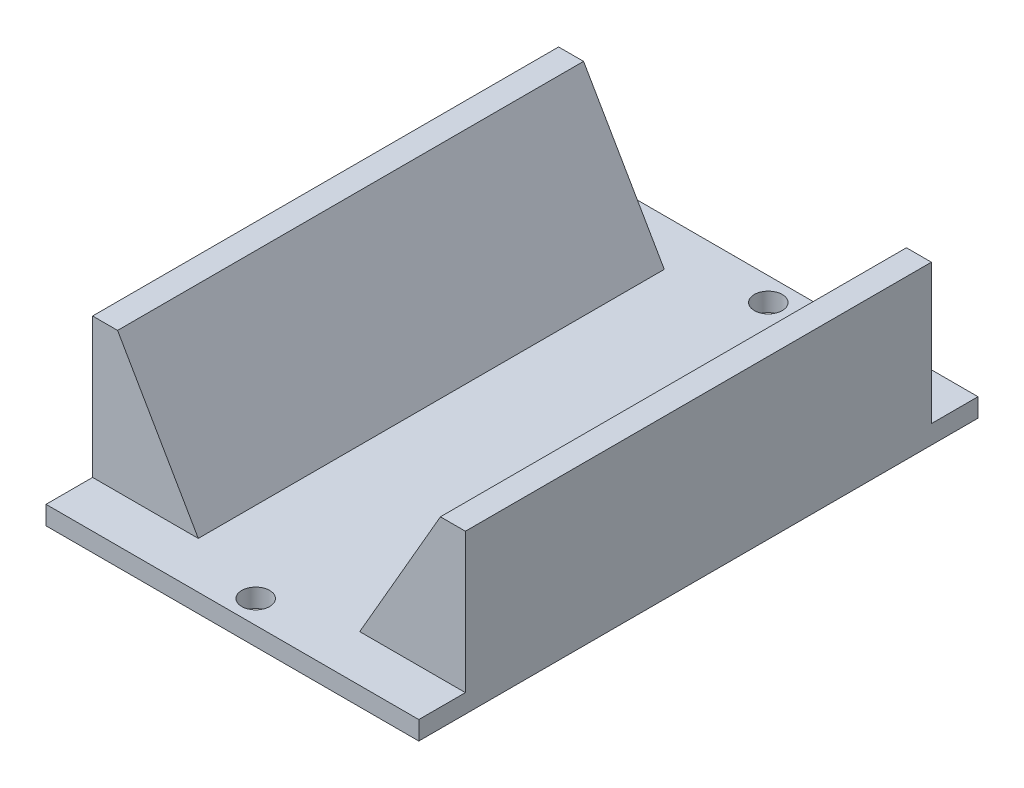
SolidWorks part; units mm, degrees
ref_plane "Front Plane" through (0, 0, 0) normal (0, 0, 1) x (1, 0, 0)
ref_plane "Top Plane" through (0, 0, 0) normal (0, 1, 0) x (1, 0, 0)
ref_plane "Right Plane" through (0, 0, 0) normal (1, 0, 0) x (0, 0, -1)
sketch "Sketch1" plane through (0, 0, 0) normal (0, 0, 1) x (1, 0, 0)
  line L0 (17.3205, 0) -> (-17.3205, 0) construction
  line L7 (8.6603, -15) -> (17.3205, 0)
  line L8 (17.3205, 0) -> (8.6603, 15) construction
  line L9 (8.6603, 15) -> (-8.6603, 15) construction
  line L10 (-8.6603, 15) -> (-17.3205, 0) construction
  line L11 (-17.3205, 0) -> (-8.6603, -15)
  line L12 (-8.6603, -15) -> (8.6603, -15)
  line L13 (-17.3205, 0) -> (-20, 0)
  line L14 (-20, 0) -> (-20, -17)
  line L15 (-20, -17) -> (20, -17)
  line L16 (20, -17) -> (20, 0)
  line L17 (20, 0) -> (17.3205, 0)
  dimension "D1" = 17
  dimension "D2" = 40
  dimension "D3" = 20
  dimension "D4" = 15
  dimension "D5" = 120
  dimension "D6" = 120
extrude "Boss-Extrude1" add sketch "Sketch1" along normal blind 50
sketch "Sketch3" plane through (0, 0, 50) normal (0, 0, 1) x (1, 0, 0)
  line L0 (20, -17) -> (20, 0) construction
  line L1 (-20, -17) -> (20, -17)
  line L2 (-20, -17) -> (-20, -15)
  line L3 (-20, -15) -> (20, -15)
  line L4 (20, -17) -> (20, -15)
  line L5 (8.6603, -15) -> (-8.6603, -15) construction
  dimension "D1" = 0
extrude "Boss-Extrude2" add sketch "Sketch3" along normal blind 5
sketch "Sketch4" plane through (0, -15, 0) normal (0, 1, 0) x (1, 0, 0)
  line L0 (-20, -55) -> (-20, -50) construction
  line L2 (20, -55) -> (-20, -55) construction
  circle A0 centre (0, -52.5) radius 1.5
  dimension "D1" = 3
  dimension "D2" = 20
  dimension "D3" = 2.5
extrude "Cut-Extrude1" cut sketch "Sketch4" against normal up to next
ref_plane "Plane1" through (0, 0, 25) normal (0, 0, 1) x (1, 0, 0)
mirror "Mirror1" about plane through (0, 0, 25) normal (0, 0, 1) of "Cut-Extrude1", "Boss-Extrude2"
